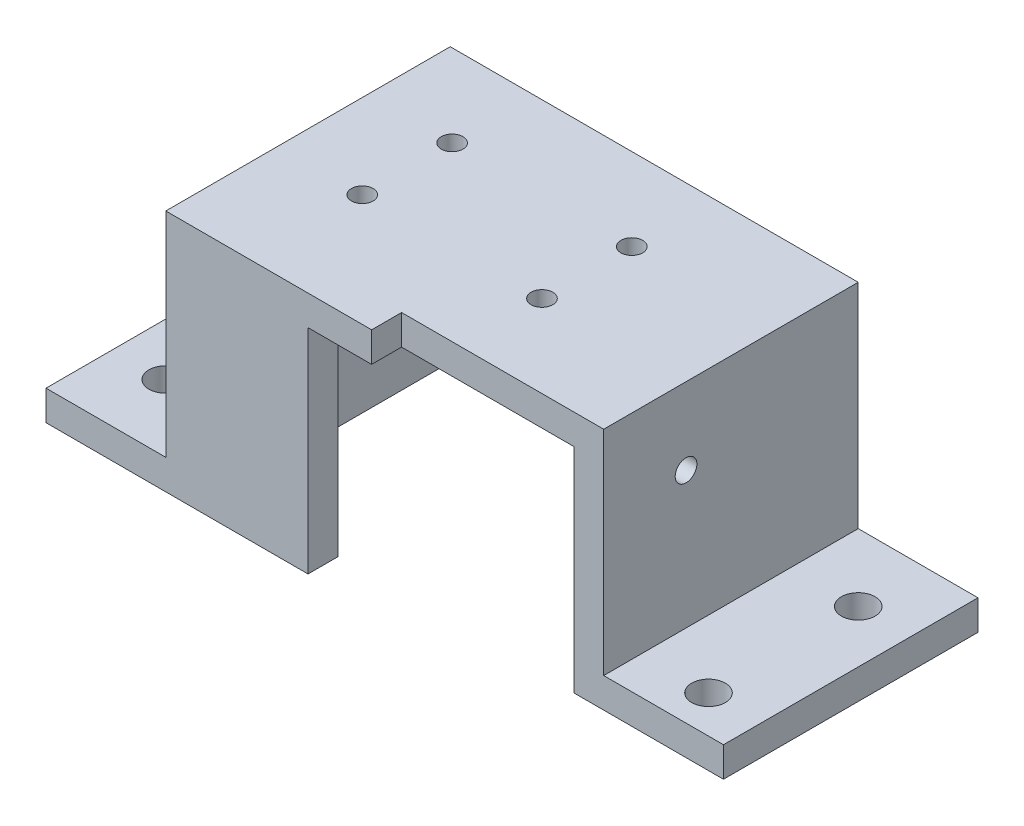
SolidWorks part; units mm, degrees
ref_plane "정면" through (0, 0, 0) normal (0, 0, 1) x (1, 0, 0)
ref_plane "윗면" through (0, 0, 0) normal (0, 1, 0) x (1, 0, 0)
ref_plane "우측면" through (0, 0, 0) normal (1, 0, 0) x (0, 0, -1)
sketch "스케치31" plane through (0, 0, 0) normal (0, 1, 0) x (1, 0, 0)
  line L1 (-27.25, 19) -> (27.25, 19)
  line L2 (-27.25, 19) -> (-27.25, -19)
  line L3 (-27.25, -19) -> (27.25, -19)
  line L4 (27.25, 19) -> (27.25, -19)
  line L5 (-27.25, 19) -> (27.25, -19) construction
  line L6 (-27.25, -19) -> (27.25, 19) construction
  point P0 (0, 0)
  dimension "D1" = 54.5
  dimension "D2" = 38
extrude "보스-돌출11" add sketch "스케치31" along normal blind 4
sketch "스케치32" plane through (0, 0, 0) normal (0, -1, 0) x (1, 0, 0)
  line L0 (27.25, -19) -> (-27.25, -19) construction
  line L1 (27.25, 19) -> (23.25, 19)
  line L2 (27.25, 19) -> (27.25, -19)
  line L3 (27.25, -19) -> (23.25, -19)
  line L4 (23.25, 19) -> (23.25, -19)
  line L6 (-27.25, 19) -> (-23.25, 19)
  line L7 (-27.25, 19) -> (-27.25, -19)
  line L8 (-27.25, -19) -> (-23.25, -19)
  line L9 (-23.25, 19) -> (-23.25, -19)
  dimension "D1" = 4
  dimension "D2" = 4
extrude "보스-돌출12" add sketch "스케치32" along normal blind 28.5
sketch "스케치33" plane through (0, -28.5, 0) normal (0, -1, 0) x (1, 0, 0)
  line L0 (0, 0) -> (0, 23.6607) construction
  line L1 (-27.25, 19) -> (-43.25, 19)
  line L2 (-27.25, 19) -> (-27.25, -19)
  line L3 (-27.25, -19) -> (-43.25, -19)
  line L4 (-43.25, 19) -> (-43.25, -19)
  line L5 (27.25, -19) -> (43.25, -19)
  line L6 (43.25, 19) -> (43.25, -19)
  line L7 (27.25, 19) -> (43.25, 19)
  line L8 (27.25, 19) -> (27.25, -19)
  dimension "D1" = 16
extrude "보스-돌출13" add sketch "스케치33" against normal blind 4
sketch "스케치34" plane through (0, 0, 0) normal (0, -1, 0) x (1, 0, 0)
  line L5 (-23.25, 19) -> (-8.25, 19)
  line L6 (-23.25, 19) -> (-23.25, 15)
  line L7 (-23.25, 15) -> (-8.25, 15)
  line L8 (-8.25, 19) -> (-8.25, 15)
  dimension "D1" = 4
  dimension "D2" = 15
extrude "보스-돌출14" add sketch "스케치34" along normal blind 28.5
hole_wizard "M2.5 여유 구멍1" positions "스케치38" profile "스케치39" hole size "M2.5" standard "ISO"
sketch "스케치38" plane through (0, 4, 0) normal (0, 1, 0) x (1, 0, 0)
  line L2 (-4, 27.2808) -> (-4, 9.8456) construction
  line L4 (5.5473, 2) -> (18.3975, 2) construction
  line L6 (27.25, 19) -> (-27.25, 19) construction
  point P0 (8, 8)
  point P9 (8, -4)
  point P13 (-16, -4)
  point P14 (-16, 8)
  dimension "D1" = 17
  dimension "D2" = 15.25
  dimension "D3" = 12
  dimension "D4" = 6
  dimension "D5" = 6
sketch "스케치39" plane through (8, 4, -8) normal (1, 0, 0) x (0, 0, 1)
  line L0 (0, 0) -> (0, 10.8712)
  line L1 (0, 10.8712) -> (1.45, 10)
  line L2 (1.45, 10) -> (1.45, 0)
  line L5 (1.45, 0) -> (0, 0)
  line L10 (0, 10.8712) -> (-1.45, 10) construction
  line L11 (0, -6.35) -> (0, 107.95) construction
  dimension "구멍 지름" = 2.9
  dimension "구멍 깊이" = 10
  dimension "드릴 각도" = 118
hole_wizard "M2.5 여유 구멍2" positions "스케치40" profile "스케치41" hole size "M2.5" standard "ISO"
sketch "스케치40" plane through (27.25, 0, 0) normal (1, 0, 0) x (0, 0, -1)
  line L0 (2, 10.9836) -> (2, -4.9718) construction
  line L2 (19, 4) -> (19, -24.5) construction
  line L3 (12.3418, -14.25) -> (24.097, -14.25) construction
  point P0 (-4, -6.25)
  point P13 (0, 0)
  dimension "D1" = 17
  dimension "D2" = 6
  dimension "D3" = 14.25
sketch "스케치41" plane through (27.25, -6.25, 4) normal (0, 1, 0) x (0, 0, -1)
  line L0 (0, 0) -> (0, 10.8712)
  line L1 (0, 10.8712) -> (1.45, 10)
  line L2 (1.45, 10) -> (1.45, 0)
  line L5 (1.45, 0) -> (0, 0)
  line L10 (0, 10.8712) -> (-1.45, 10) construction
  line L11 (0, -6.35) -> (0, 107.95) construction
  dimension "구멍 지름" = 2.9
  dimension "구멍 깊이" = 10
  dimension "드릴 각도" = 118
hole_wizard "M2.5 여유 구멍3" positions "스케치42" profile "스케치43" hole size "M2.5" standard "ISO"
sketch "스케치42" plane through (-27.25, 0, 0) normal (-1, 0, 0) x (0, 0, 1)
  line L0 (-2, 8.4663) -> (-2, -5.2284) construction
  line L2 (-19, 4) -> (-19, -24.5) construction
  line L3 (-23.7973, -14.25) -> (-6.8658, -14.25) construction
  point P0 (4, -6.25)
  point P13 (-8, -6.25)
  dimension "D1" = 17
  dimension "D2" = 6
  dimension "D3" = 14.25
  dimension "D4" = 8
sketch "스케치43" plane through (-27.25, -6.25, 4) normal (0, 1, 0) x (0, 0, 1)
  line L0 (0, 0) -> (0, 10.8712)
  line L1 (0, 10.8712) -> (1.45, 10)
  line L2 (1.45, 10) -> (1.45, 0)
  line L5 (1.45, 0) -> (0, 0)
  line L10 (0, 10.8712) -> (-1.45, 10) construction
  line L11 (0, -6.35) -> (0, 107.95) construction
  dimension "구멍 지름" = 2.9
  dimension "구멍 깊이" = 10
  dimension "드릴 각도" = 118
hole_wizard "M4 여유 구멍1" positions "스케치44" profile "스케치45" hole size "M4" standard "ISO"
sketch "스케치44" plane through (0, -24.5, 0) normal (0, 1, 0) x (1, 0, 0)
  line L0 (32.1, 0) -> (50.23, 0) construction
  line L2 (43.25, 19) -> (43.25, -19) construction
  line L3 (0, 0) -> (0, 26.7589) construction
  point P0 (36.25, 10)
  point P10 (36.25, -10)
  point P14 (-36.25, -10)
  point P15 (-36.25, 10)
  dimension "D1" = 10
  dimension "D2" = 7
sketch "스케치45" plane through (36.25, -24.5, -10) normal (1, 0, 0) x (0, 0, 1)
  line L0 (0, 0) -> (0, 11.3519)
  line L1 (0, 11.3519) -> (2.25, 10)
  line L2 (2.25, 10) -> (2.25, 0)
  line L5 (2.25, 0) -> (0, 0)
  line L10 (0, 11.3519) -> (-2.25, 10) construction
  line L11 (0, -6.35) -> (0, 107.95) construction
  dimension "구멍 지름" = 4.5
  dimension "구멍 깊이" = 10
  dimension "드릴 각도" = 118
sketch "스케치46" plane through (0, 0, 19) normal (0, 0, 1) x (1, 0, 0)
  line L0 (-27.25, 4) -> (27.25, 4) construction
  line L1 (43.25, -28.5) -> (0.25, -28.5)
  line L2 (43.25, -28.5) -> (43.25, 4)
  line L3 (43.25, 4) -> (0.25, 4)
  line L4 (0.25, -28.5) -> (0.25, 4)
  dimension "D1" = 43
extrude "컷-돌출4" cut sketch "스케치46" against normal blind 4
